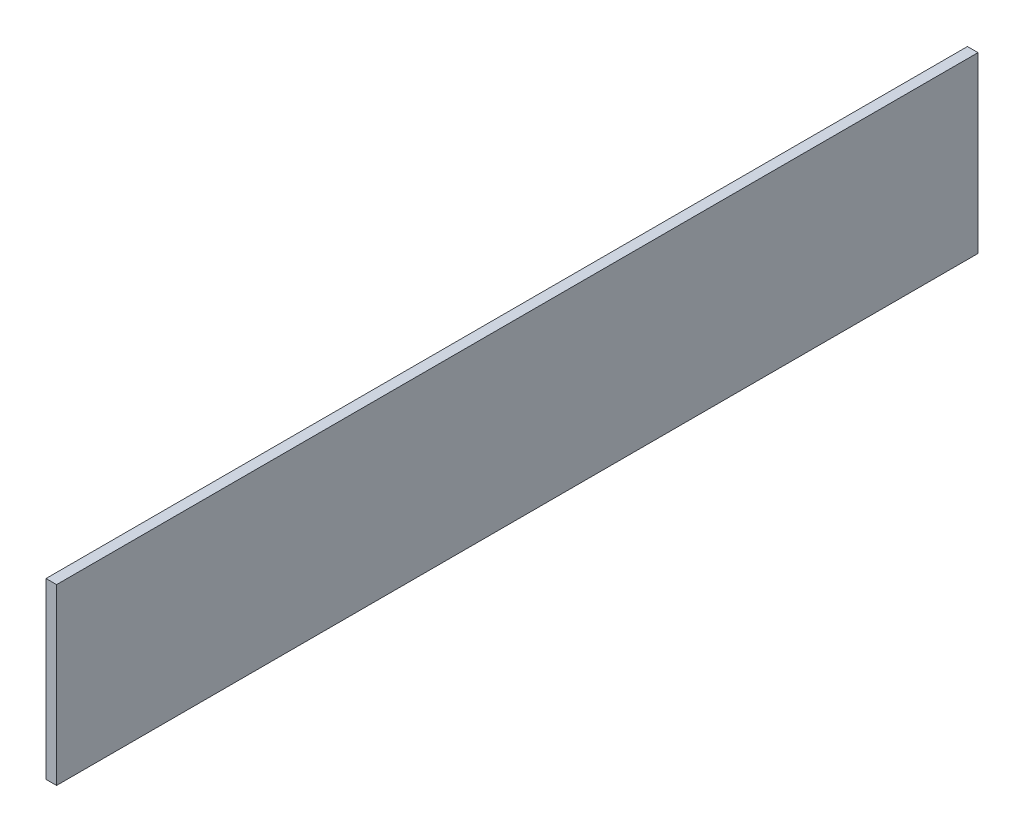
SolidWorks part; units mm, degrees
ref_plane "Front Plane" through (0, 0, 0) normal (0, 0, 1) x (1, 0, 0)
ref_plane "Top Plane" through (0, 0, 0) normal (0, 1, 0) x (1, 0, 0)
ref_plane "Right Plane" through (0, 0, 0) normal (1, 0, 0) x (0, 0, -1)
sketch "Sketch2" plane through (0, 0, 0) normal (0, 1, 0) x (1, 0, 0)
  line L0 (-105.4338, 148.3095) -> (-105.4338, -148.3095)
  line L1 (-105.4338, 148.3095) -> (105.4338, 148.3095)
  line L2 (-105.4338, 148.3095) -> (-105.4338, -148.3095)
  line L3 (-105.4338, -148.3095) -> (105.4338, -148.3095)
  line L4 (105.4338, 148.3095) -> (105.4338, -148.3095)
  line L5 (-105.4338, 148.3095) -> (105.4338, -148.3095) construction
  line L6 (-105.4338, -148.3095) -> (105.4338, 148.3095) construction
  line L7 (-105.4338, 148.3095) -> (-108.8376, 148.3095)
  line L8 (-105.4338, -148.3095) -> (-108.8376, -148.3095)
  line L9 (-108.8376, 148.3095) -> (-108.8376, -148.3095)
  point P0 (0, 0)
extrude "Boss-Extrude1" add sketch "Sketch2" along normal blind 56 contours L7 L9 L8 L0
sketch "Sketch4" plane through (0, 0, 0) normal (0, 1, 0) x (1, 0, 0)
  line L0 (-105.4338, 148.3095) -> (-105.4338, -148.3095)
  line L1 (-105.4338, 148.3095) -> (102.1006, 148.3095)
  line L2 (-105.4338, -148.3095) -> (102.1006, -148.3095)
  line L3 (102.1006, 148.3095) -> (102.1006, -148.3095)
